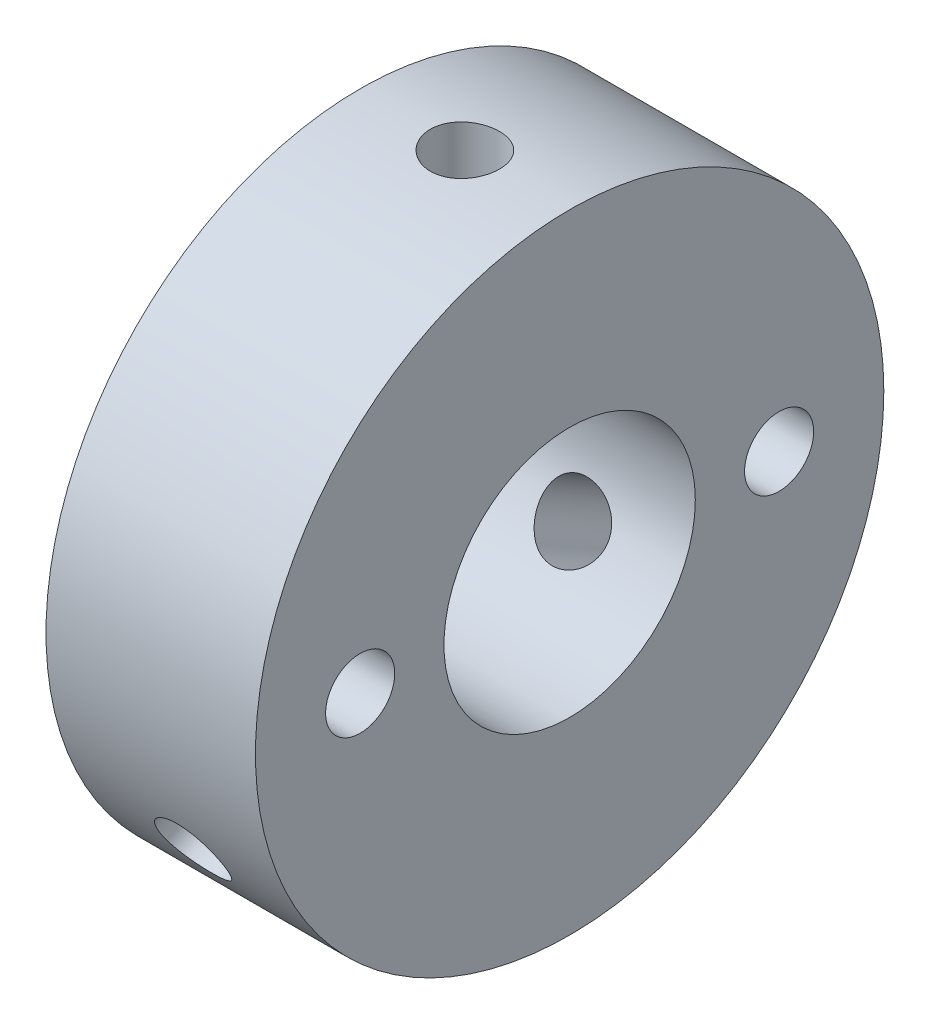
SolidWorks part; units mm, degrees
material "5052-H34"
ref_plane "正面" through (0, 0, 0) normal (0, 0, 1) x (1, 0, 0)
ref_plane "平面" through (0, 0, 0) normal (0, 1, 0) x (1, 0, 0)
ref_plane "右側面" through (0, 0, 0) normal (1, 0, 0) x (0, 0, -1)
sketch "ｽｹｯﾁ1" plane through (0, 0, 0) normal (1, 0, 0) x (0, 0, -1)
  line L0 (0, 0) -> (0, 15) construction
  line L1 (0, 0) -> (-10, 0) construction
  circle A0 centre (0, 0) radius 6
  circle A1 centre (0, 0) radius 15
  circle A2 centre (-10, 0) radius 1.65
  circle A3 centre (10, 0) radius 1.65
  dimension "D1" = 12
  dimension "D2" = 30
  dimension "D3" = 3.3
  dimension "D4" = 20
extrude "ﾎﾞｽ - 押し出し1" add sketch "ｽｹｯﾁ1" along normal blind 10
sketch "ｽｹｯﾁ2" plane through (0, 0, 0) normal (0, 1, 0) x (1, 0, 0)
  line L0 (0, 0) -> (10, 0) construction
  line L1 (10, -15) -> (10, 15) construction
  circle A0 centre (5, 0) radius 1.65
  dimension "D1" = 3.3
extrude "ｶｯﾄ - 押し出し1" cut sketch "ｽｹｯﾁ2" along normal through all
pattern_circular "円形ﾊﾟﾀｰﾝ1" count 3 over 360 about axis through (10, 0, 0) along (1, 0, 0) of "ｶｯﾄ - 押し出し1"
